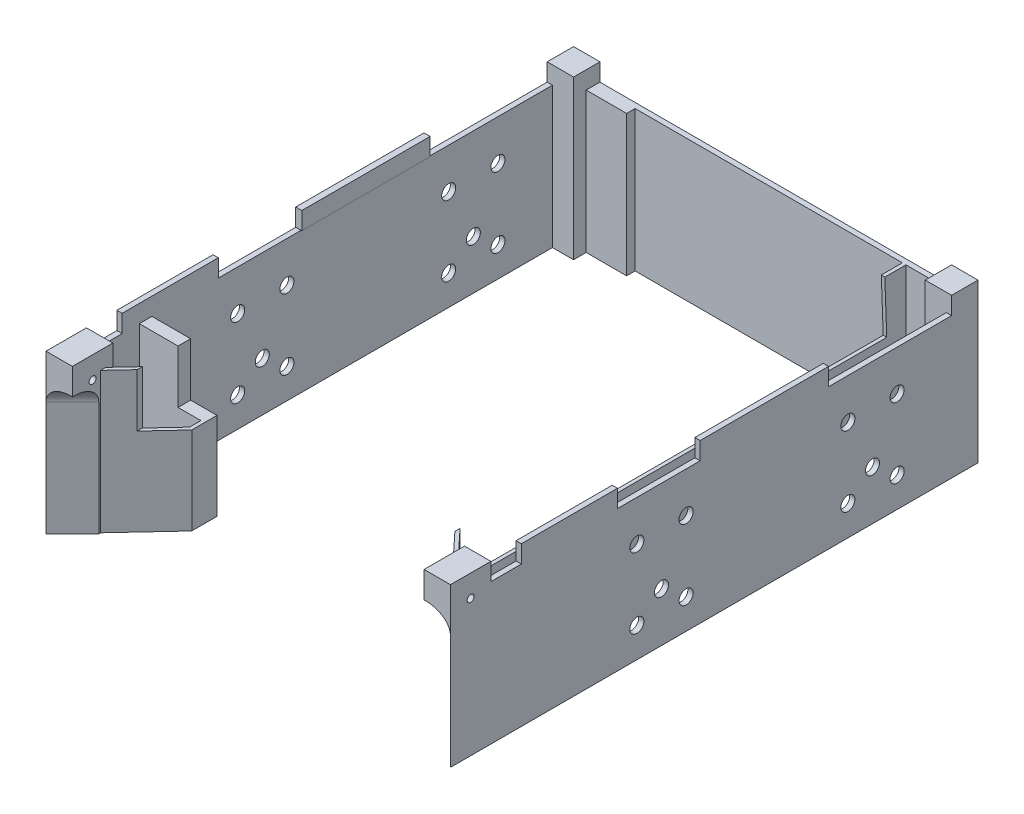
SolidWorks part; units mm, degrees
ref_plane "Front Plane" through (0, 0, 0) normal (0, 0, 1) x (1, 0, 0)
ref_plane "Top Plane" through (0, 0, 0) normal (0, 1, 0) x (1, 0, 0)
ref_plane "Right Plane" through (0, 0, 0) normal (1, 0, 0) x (0, 0, -1)
sketch "Sketch1" plane through (0, 0, 0) normal (0, 1, 0) x (1, 0, 0)
  line L0 (0, 184.6644) -> (0, -150) construction
  line L1 (-115, 150) -> (115, 150)
  line L2 (-150, 150) -> (-150, -150) construction
  line L4 (150, 150) -> (150, -149.1635) construction
  line L5 (-150, 150) -> (0, 0) construction
  line L6 (-112, -112) -> (150, 150) construction
  line L7 (-147, 147) -> (-115, 147) construction
  line L8 (-147, 147) -> (-147, -147) construction
  line L10 (-115, 147) -> (-115, -92.7574)
  line L16 (147, 147) -> (147, -147) construction
  line L17 (147, 147) -> (115, 147) construction
  line L21 (-112, 142.1766) -> (-112, -92.7574)
  line L23 (112, 147) -> (112, -112)
  line L32 (-147, -147) -> (-115, -147) construction
  line L33 (-112, -112) -> (-112, -143.8514)
  line L34 (-115, -92.7574) -> (-115, -147)
  line L35 (112, -112) -> (112, -143.8514)
  line L38 (115, -147) -> (147, -147) construction
  line L39 (-115, -147) -> (-115, -150)
  line L40 (-115, 147) -> (-115, 150)
  line L43 (-75, -92.7574) -> (-75, -107.1152)
  line L44 (-77, 147) -> (-77, 142.1766)
  line L45 (-75, 147) -> (75, 147)
  line L46 (-75, -107.1152) -> (-115, -150)
  line L47 (-112, -143.8514) -> (-77, -106.3272)
  line L48 (-77, 147) -> (-77, -107.1152) construction
  line L49 (-112, -92.7574) -> (-75, -92.7574)
  line L50 (75, 147) -> (75, -107.1152)
  line L51 (77, 147) -> (77, -106.3272)
  line L52 (112, -143.8514) -> (77, -106.3272)
  line L53 (75, -107.1152) -> (115, -150)
  line L54 (77, 147) -> (112, 147)
  line L55 (115, 150) -> (115, -150)
  line L56 (-112, -99.9206) -> (-77, -99.9206)
  line L57 (-112, -99.9206) -> (-112, -112)
  line L58 (-77, -99.9206) -> (-77, -106.3272)
  line L59 (-112, 142.1766) -> (-77, 142.1766)
  line L60 (-75, 147) -> (-75, -107.1152) construction
  line L62 (-75, 147) -> (-77, 147)
  point P0 (0, 0)
  dimension "D1" = 300
  dimension "D2" = 3
  dimension "50" = 32
  dimension "D3" = 35
  dimension "3" = 3
  dimension "D5" = 2
  dimension "D6" = 3
  dimension "D7" = 2
extrude "Boss-Extrude1" add sketch "Sketch1" along normal blind 80
sketch "Sketch2" plane through (0, 0, 0) normal (1, 0, 0) x (0, 0, -1)
  line L0 (94, 28) -> (86, 28) construction
  line L8 (-26, 28) -> (-34, 28) construction
  line L9 (150, 28) -> (-150, 28) construction
  line L10 (150, 80) -> (150, 0) construction
  line L11 (-150, 80) -> (-150, 0) construction
  line L12 (-150, 0) -> (150, 0) construction
  circle A3 centre (90, 28) radius 4
  circle A4 centre (-30, 28) radius 4
  dimension "D1" = 28
  dimension "D2" = 60
  dimension "D5" = 8
  dimension "D8" = 120
  dimension "D9" = 8
extrude "Cut-Extrude1" cut sketch "Sketch2" against normal through all both and the other way through all
sketch "Sketch5" plane through (0, 0, 0) normal (0, 1, 0) x (1, 0, 0)
  line L1 (-115, -127) -> (-100, -127)
  line L2 (-115, -127) -> (-115, -140.4272)
  line L4 (-100, -127) -> (-100, -135)
  line L6 (-115, -140.4272) -> (-115, -150)
  line L7 (-115, -150) -> (-100, -135)
  line L8 (0, 0) -> (0, -201.0806) construction
  line L9 (115, -150) -> (100, -135)
  line L10 (115, -140.4272) -> (115, -150)
  line L11 (100, -127) -> (100, -135)
  line L12 (115, -127) -> (115, -140.4272)
  line L13 (115, -127) -> (100, -127)
  line L14 (100, 150) -> (100, 135)
  line L15 (-115, 150) -> (-100, 150)
  line L16 (-115, 150) -> (-115, 135)
  line L17 (-115, 135) -> (-100, 135)
  line L18 (-100, 150) -> (-100, 135)
  line L19 (115, 135) -> (100, 135)
  line L20 (115, 150) -> (115, 135)
  line L21 (115, 150) -> (100, 150)
  dimension "D1" = 15
  dimension "D2" = 15
  dimension "D3" = 15
  dimension "D4" = 8
extrude "Boss-Extrude2" add sketch "Sketch5" along normal blind 90
sketch "Sketch6" plane through (-112, 0, 0) normal (1, 0, 0) x (0, 0, -1)
  line L0 (90, 28) -> (70.003, 8.003) construction
  line L1 (70.003, 66.003) -> (110.003, 66.003) construction
  line L2 (70.003, 66.003) -> (70.003, 8.003) construction
  line L3 (70.003, 8.003) -> (110.003, 8.003) construction
  line L4 (110.003, 66.003) -> (110.003, 8.003) construction
  line L5 (90, 28) -> (110.003, 8.003) construction
  line L6 (90.2932, 17) -> (139.9425, 17) construction
  line L7 (90.2932, 37) -> (139.9425, 37) construction
  line L8 (76, 60.0985) -> (76, 3.4453) construction
  line L9 (104, 60.0985) -> (104, 3.4453) construction
  line L10 (90, 28) -> (-30, 28) construction
  line L11 (30, 28) -> (30, 63.4779) construction
  line L12 (-30, 28) -> (-50.003, 8.003) construction
  line L13 (-50.003, 66.003) -> (-50.003, 8.003) construction
  line L14 (-10.003, 8.003) -> (-50.003, 8.003) construction
  line L15 (-10.003, 66.003) -> (-10.003, 8.003) construction
  line L16 (-10.003, 66.003) -> (-50.003, 66.003) construction
  line L17 (-30, 28) -> (-10.003, 8.003) construction
  circle A1 centre (76, 17) radius 4
  circle A2 centre (104, 17) radius 4
  circle A3 centre (104, 57) radius 4
  circle A4 centre (76, 57) radius 4
  circle A5 centre (-16, 57) radius 4
  circle A6 centre (-44, 57) radius 4
  circle A7 centre (-44, 17) radius 4
  circle A8 centre (-16, 17) radius 4
  dimension "D1" = 58
  dimension "D11" = 8
  dimension "D12" = 8
  dimension "D2" = 40
  dimension "D3" = 45
  dimension "D4" = 28.28
  dimension "D5" = 28.2843
  dimension "D6" = 44.991
  dimension "D7" = 9
  dimension "D8" = 11
  dimension "D9" = 14
  dimension "D10" = 14
extrude "Cut-Extrude2" cut sketch "Sketch6" against normal blind 10 and the other way blind 230
sketch "Sketch7" plane through (0, 0, 0) normal (1, 0, 0) x (0, 0, -1)
  line L0 (-127, 80) -> (-127, 49.7553)
  line L1 (-127, 49.7553) -> (136.1001, 49.7553)
  line L2 (136.1001, 49.7553) -> (135, 80)
  line L3 (135, 80) -> (-127, 80)
extrude "Cut-Extrude3" cut sketch "Sketch7" against normal blind 90 and the other way blind 80
sketch "Sketch8" plane through (0, 90, 0) normal (0, 1, 0) x (1, 0, 0)
  line L0 (115, -150) -> (115, -127) construction
  line L1 (100, -127) -> (115, -127)
  line L2 (100, -127) -> (100, -150)
  line L3 (100, -150) -> (115, -150)
  line L4 (115, -127) -> (115, -150)
  line L6 (-115, -150) -> (-100, -150)
  line L7 (-115, -150) -> (-115, -127)
  line L8 (-115, -127) -> (-100, -127)
  line L9 (-100, -150) -> (-100, -127)
extrude "Boss-Extrude3" add sketch "Sketch8" against normal blind 15
fillet "Fillet1" radius 10 1 edges at (107.5, 75, 142.5)
fillet "Fillet2" radius 10 1 edges at (-107.5, 75, 142.5)
sketch "Sketch9" plane through (100, 0, 0) normal (-1, 0, 0) x (0, 0, 1)
  line L1 (127, 90) -> (150, 90)
  line L2 (127, 90) -> (127, 65)
  line L3 (127, 65) -> (150, 65)
  line L4 (150, 90) -> (150, 65)
  circle A0 centre (138.5, 77.5) radius 2
  dimension "D2" = 4
  dimension "D1" = 25
extrude "Cut-Extrude5" cut sketch "Sketch9" against normal through all and the other way blind 245 contours A0
sketch "Sketch11" plane through (0, 80, 0) normal (0, 1, 0) x (1, 0, 0)
  line L0 (-115, -8) -> (-65, -8) construction
  line L1 (-115, 65) -> (-111.5366, 65)
  line L2 (-115, 65) -> (-115, -8)
  line L3 (-115, -8) -> (-111.5366, -8)
  line L4 (-111.5366, 65) -> (-111.5366, -8)
  line L5 (65, -8) -> (115, -8) construction
  line L6 (115, 65) -> (112, 65)
  line L7 (115, 65) -> (115, -8)
  line L8 (115, -8) -> (112, -8)
  line L9 (112, 65) -> (112, -8)
  line L10 (112, -127) -> (112, 135) construction
  line L11 (-112, 135) -> (-112, -92.7574) construction
  line L12 (-115, -55) -> (-112, -55)
  line L13 (-115, -55) -> (-115, -109.7096)
  line L14 (-115, -109.7096) -> (-112, -109.7096)
  line L15 (-112, -55) -> (-112, -109.7096)
  line L17 (115, -55) -> (112, -55)
  line L18 (115, -55) -> (115, -109.7096)
  line L19 (115, -109.7096) -> (112, -109.7096)
  line L20 (112, -55) -> (112, -109.7096)
extrude "Boss-Extrude4" add sketch "Sketch11" along normal through all
